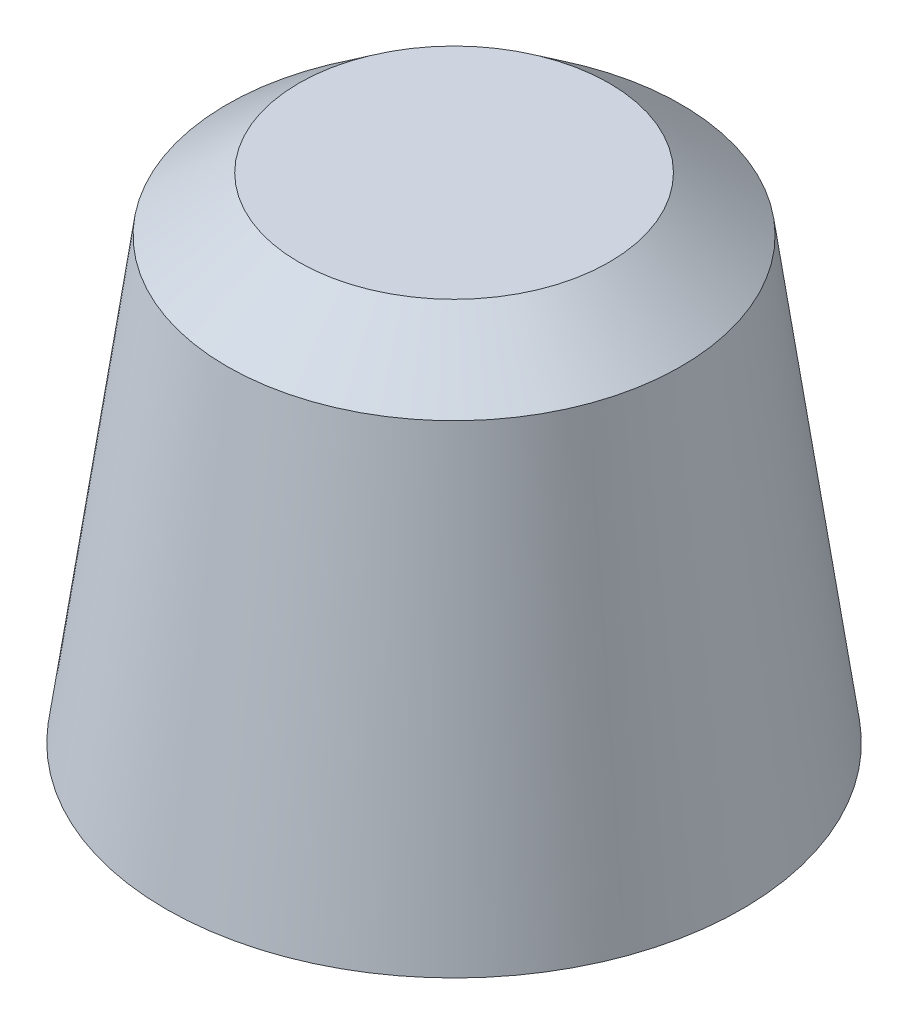
SolidWorks part; units mm, degrees
material "ABS"
ref_plane "Piano frontale" through (0, 0, 0) normal (0, 0, 1) x (1, 0, 0)
ref_plane "Piano superiore" through (0, 0, 0) normal (0, 1, 0) x (1, 0, 0)
ref_plane "Piano destro" through (0, 0, 0) normal (1, 0, 0) x (0, 0, -1)
ref_plane "Piano1" through (0, 9, 0) normal (0, 1, 0) x (1, 0, 0)
sketch "Schizzo1" plane through (0, 0, 0) normal (0, 1, 0) x (1, 0, 0)
  circle A0 centre (0, 0) radius 5.25
  dimension "D1" = 10.5
sketch "Schizzo2" plane through (0, 9, 0) normal (0, 1, 0) x (1, 0, 0)
  circle A0 centre (0, 0) radius 4
  dimension "D1" = 8
loft "Loft1" add profiles "Schizzo1", "Schizzo2"
chamfer "Smusso1" distance 1 angle 45 1 edges at (0, 9, 4)
sketch "Schizzo3" plane through (0, 0, 0) normal (0, -1, 0) x (-1, 0, 0)
  point P0 (0, 0)
hole_wizard "Foro per Vite M3-1" positions "Schizzo3" profile "Schizzo4" hole size "M3" standard "ISO"
sketch "Schizzo4" plane through (0, 0, 0) normal (1, 0, 0) x (0, 0, -1)
  line L0 (0, 0) -> (0, 8.6223)
  line L1 (0, 8.6223) -> (2.7, 7)
  line L2 (2.7, 7) -> (2.7, 0)
  line L5 (2.7, 0) -> (0, 0)
  line L10 (0, 8.6223) -> (-2.7, 7) construction
  line L11 (0, -6.35) -> (0, 107.95) construction
  dimension "Hole Dia." = 5.4
  dimension "Hole Depth" = 7
  dimension "Drill Angle" = 118
